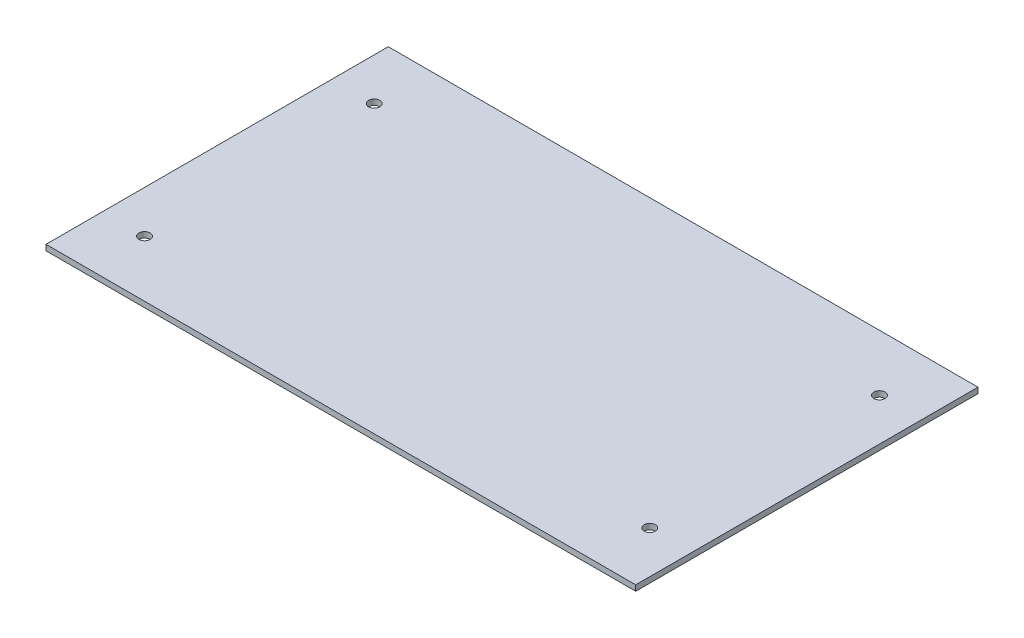
SolidWorks part; units mm, degrees
material "1060 Alloy"
ref_plane "Front Plane" through (0, 0, 0) normal (0, 0, 1) x (1, 0, 0)
ref_plane "Top Plane" through (0, 0, 0) normal (0, 1, 0) x (1, 0, 0)
ref_plane "Right Plane" through (0, 0, 0) normal (1, 0, 0) x (0, 0, -1)
sketch "Sketch1" plane through (0, 0, 0) normal (0, 1, 0) x (1, 0, 0)
  line L1 (-77.5877, 32.8522) -> (131.9123, 32.8522)
  line L2 (-77.5877, 32.8522) -> (-77.5877, -88.7478)
  line L3 (-77.5877, -88.7478) -> (131.9123, -88.7478)
  line L4 (131.9123, 32.8522) -> (131.9123, -88.7478)
  dimension "D1" = 209.5
  dimension "D2" = 121.6
extrude "Boss-Extrude1" add sketch "Sketch1" along normal blind 2
sketch "Sketch2" plane through (0, 2, 0) normal (0, 1, 0) x (1, 0, 0)
  line L0 (131.9123, 32.8522) -> (-77.5877, 32.8522) construction
  line L1 (131.9123, -88.7478) -> (131.9123, 32.8522) construction
  line L2 (-77.5877, 32.8522) -> (-77.5877, -88.7478) construction
  circle A0 centre (-62.5877, 12.8522) radius 2
  circle A1 centre (116.9123, 12.8522) radius 2
  circle A2 centre (-62.5877, -68.7478) radius 2
  circle A3 centre (116.9123, -68.7478) radius 2
  dimension "D1" = 179.5
  dimension "D2" = 4
  dimension "D3" = 4
  dimension "D5" = 15
  dimension "D6" = 20
  dimension "D7" = 4
  dimension "D8" = 4
  dimension "D9" = 81.6
  dimension "D10" = 81.6
  dimension "D11" = 15
  dimension "D12" = 15
  dimension "D4" = 20
extrude "Cut-Extrude1" cut sketch "Sketch2" against normal through all both and the other way through all
